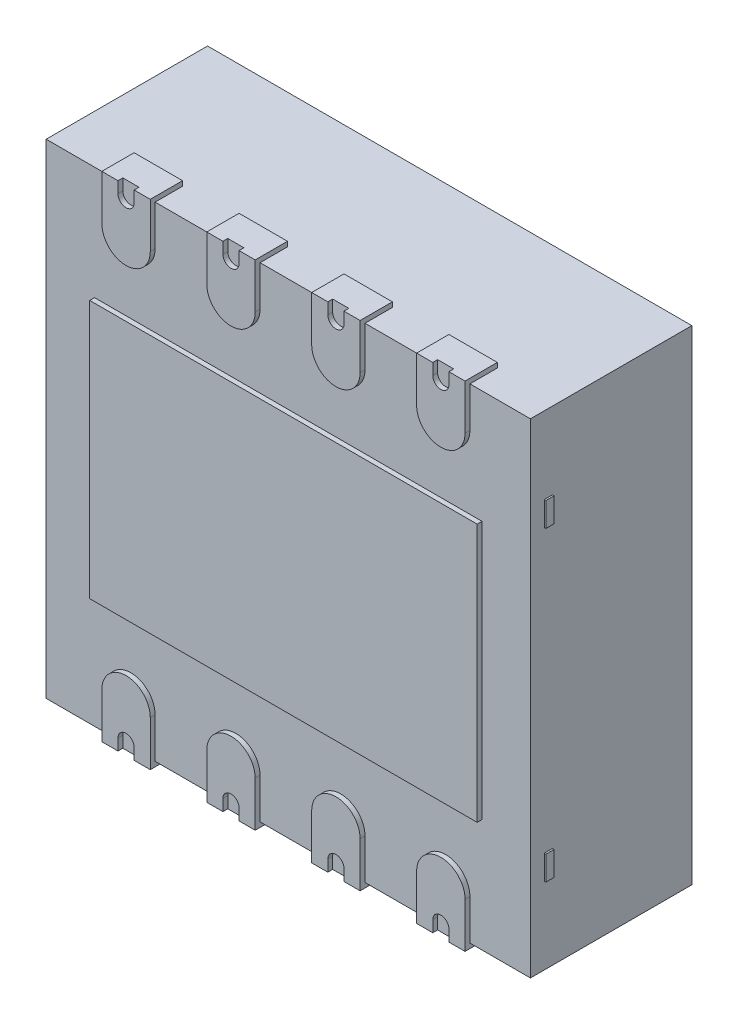
SolidWorks part; units mm, degrees
ref_plane "Front Plane" through (0, 0, 0) normal (0, 0, 1) x (1, 0, 0)
ref_plane "Top Plane" through (0, 0, 0) normal (0, 1, 0) x (1, 0, 0)
ref_plane "Right Plane" through (0, 0, 0) normal (1, 0, 0) x (0, 0, -1)
sketch "Sketch1" plane through (0, 0, 0) normal (0, 0, 1) x (1, 0, 0)
  line L1 (1.5, 1.5) -> (-1.5, 1.5)
  line L2 (1.5, 1.5) -> (1.5, -1.5)
  line L3 (1.5, -1.5) -> (-1.5, -1.5)
  line L4 (-1.5, 1.5) -> (-1.5, -1.5)
  line L5 (1.5, 1.5) -> (-1.5, -1.5) construction
  line L6 (1.5, -1.5) -> (-1.5, 1.5) construction
  point P0 (0, 0)
  dimension "D1" = 3
  dimension "D2" = 3
extrude "Boss-Extrude1" add sketch "Sketch1" against normal blind 1
sketch "Sketch2" plane through (0, 0, 0) normal (0, 0, 1) x (-1, 0, 0)
  line L0 (-0.975, 1.25) -> (-0.975, 1.6035) construction
  line L1 (1.2, 0.8) -> (-1.2, 0.8)
  line L2 (1.2, 0.8) -> (1.2, -0.8)
  line L3 (1.2, -0.8) -> (-1.2, -0.8)
  line L4 (-1.2, 0.8) -> (-1.2, -0.8)
  line L5 (1.2, 0.8) -> (-1.2, -0.8) construction
  line L6 (1.2, -0.8) -> (-1.2, 0.8) construction
  line L7 (-1.125, 1.25) -> (-1.125, 1.6035)
  line L8 (-0.825, 1.25) -> (-0.825, 1.6035)
  line L9 (1.5, 1.5) -> (-1.5, 1.5) construction
  line L10 (-0.175, 1.25) -> (-0.175, 1.6035)
  line L11 (-0.475, 1.25) -> (-0.475, 1.6035)
  line L12 (-0.325, 1.25) -> (-0.325, 1.6035) construction
  line L13 (0.475, 1.25) -> (0.475, 1.6035)
  line L14 (0.175, 1.25) -> (0.175, 1.6035)
  line L15 (0.325, 1.25) -> (0.325, 1.6035) construction
  line L16 (1.125, 1.25) -> (1.125, 1.6035)
  line L17 (0.825, 1.25) -> (0.825, 1.6035)
  line L18 (0.975, 1.25) -> (0.975, 1.6035) construction
  line L19 (0, 0) -> (0.825, 0) construction
  line L20 (-0.975, -1.25) -> (-0.975, -1.6035) construction
  line L21 (-1.125, -1.25) -> (-1.125, -1.6035)
  line L22 (-0.825, -1.25) -> (-0.825, -1.6035)
  line L23 (-0.325, -1.25) -> (-0.325, -1.6035) construction
  line L24 (-0.475, -1.25) -> (-0.475, -1.6035)
  line L25 (-0.175, -1.25) -> (-0.175, -1.6035)
  line L26 (0.325, -1.25) -> (0.325, -1.6035) construction
  line L27 (0.175, -1.25) -> (0.175, -1.6035)
  line L28 (0.475, -1.25) -> (0.475, -1.6035)
  line L29 (0.975, -1.25) -> (0.975, -1.6035) construction
  line L30 (0.825, -1.25) -> (0.825, -1.6035)
  line L31 (1.125, -1.25) -> (1.125, -1.6035)
  arc A0 (-1.125, 1.25) -> (-0.825, 1.25) centre (-0.975, 1.25) ccw
  arc A1 (-0.825, 1.6035) -> (-1.125, 1.6035) centre (-0.975, 1.6035) ccw
  arc A2 (-0.475, 1.25) -> (-0.175, 1.25) centre (-0.325, 1.25) ccw
  arc A3 (-0.175, 1.6035) -> (-0.475, 1.6035) centre (-0.325, 1.6035) ccw
  arc A4 (0.175, 1.25) -> (0.475, 1.25) centre (0.325, 1.25) ccw
  arc A5 (0.475, 1.6035) -> (0.175, 1.6035) centre (0.325, 1.6035) ccw
  arc A6 (0.825, 1.25) -> (1.125, 1.25) centre (0.975, 1.25) ccw
  arc A7 (1.125, 1.6035) -> (0.825, 1.6035) centre (0.975, 1.6035) ccw
  arc A8 (-1.125, -1.25) -> (-0.825, -1.25) centre (-0.975, -1.25) cw
  arc A9 (-0.825, -1.6035) -> (-1.125, -1.6035) centre (-0.975, -1.6035) cw
  arc A10 (-0.475, -1.25) -> (-0.175, -1.25) centre (-0.325, -1.25) cw
  arc A11 (-0.175, -1.6035) -> (-0.475, -1.6035) centre (-0.325, -1.6035) cw
  arc A12 (0.175, -1.25) -> (0.475, -1.25) centre (0.325, -1.25) cw
  arc A13 (0.475, -1.6035) -> (0.175, -1.6035) centre (0.325, -1.6035) cw
  arc A14 (0.825, -1.25) -> (1.125, -1.25) centre (0.975, -1.25) cw
  arc A15 (1.125, -1.6035) -> (0.825, -1.6035) centre (0.975, -1.6035) cw
  point P0 (0, 0)
  point P8 (-0.975, 1.4268)
  point P13 (-0.975, 1.1)
  point P19 (-0.325, 1.4268)
  point P26 (0.325, 1.4268)
  point P33 (0.975, 1.4268)
  point P41 (-0.975, -1.4268)
  point P48 (-0.325, -1.4268)
  point P55 (0.325, -1.4268)
  point P62 (0.975, -1.4268)
  dimension "D1" = 1.6
  dimension "D2" = 2.4
  dimension "D3" = 0.3
  dimension "D4" = 0.4
  dimension "D5" = 0.975
  dimension "D6" = 4
extrude "Boss-Extrude2" add sketch "Sketch2" along normal blind 0.03
sketch "Sketch4" plane through (0, 0, -1) normal (0, 0, -1) x (-1, 0, 0)
  line L1 (1.5, 1.5) -> (-1.5, 1.5)
  line L2 (1.5, 1.5) -> (1.5, -1.5)
  line L3 (1.5, -1.5) -> (-1.5, -1.5)
  line L4 (-1.5, 1.5) -> (-1.5, -1.5)
  line L5 (-2.0468, 1.8988) -> (1.8937, 1.8988)
  line L6 (-2.0468, 1.8988) -> (-2.0468, -1.9448)
  line L7 (-2.0468, -1.9448) -> (1.8937, -1.9448)
  line L8 (1.8937, 1.8988) -> (1.8937, -1.9448)
extrude "Cut-Extrude1" cut sketch "Sketch4" against normal blind 60.05
sketch "Sketch7" plane through (0, -1.5, 0) normal (0, -1, 0) x (1, 0, 0)
  line L0 (0.825, 0.03) -> (0.825, 0) construction
  line L1 (1.125, -0.17) -> (0.825, -0.17)
  line L2 (1.125, -0.17) -> (1.125, 0.03)
  line L3 (1.125, 0.03) -> (0.825, 0.03)
  line L4 (0.825, -0.17) -> (0.825, 0.03)
  line L5 (0.175, 0.03) -> (0.175, 0) construction
  line L6 (0.475, -0.17) -> (0.175, -0.17)
  line L7 (0.475, -0.17) -> (0.475, 0.03)
  line L8 (0.475, 0.03) -> (0.175, 0.03)
  line L9 (0.175, -0.17) -> (0.175, 0.03)
  line L10 (-0.475, 0.03) -> (-0.475, 0) construction
  line L11 (-0.175, -0.17) -> (-0.475, -0.17)
  line L12 (-0.175, -0.17) -> (-0.175, 0.03)
  line L13 (-0.175, 0.03) -> (-0.475, 0.03)
  line L14 (-0.475, -0.17) -> (-0.475, 0.03)
  line L15 (-1.125, 0.03) -> (-1.125, 0) construction
  line L16 (-0.825, -0.17) -> (-1.125, -0.17)
  line L17 (-0.825, -0.17) -> (-0.825, 0.03)
  line L18 (-0.825, 0.03) -> (-1.125, 0.03)
  line L19 (-1.125, -0.17) -> (-1.125, 0.03)
  point P7 (0.825, 0.015)
  point P22 (-0.475, 0.015)
  dimension "D1" = 0
  dimension "D2" = 0
  dimension "D3" = 0
  dimension "D4" = 0
  dimension "D5" = 0.2
  dimension "D6" = 0.2
  dimension "D7" = 0.2
  dimension "D8" = 0.2
extrude "Boss-Extrude3" add sketch "Sketch7" along normal blind 0.03
mirror "Mirror1" about plane through (0, 0, 0) normal (0, 1, 0) of "Boss-Extrude3"
sketch "Sketch8" plane through (0, 0, 0.03) normal (0, 0, 1) x (-1, 0, 0)
  line L0 (-0.975, 1.6098) -> (-0.975, 1.4598) construction
  line L1 (-0.925, 1.6098) -> (-0.925, 1.4598)
  line L2 (-1.025, 1.6098) -> (-1.025, 1.4598)
  line L3 (-0.375, 1.6098) -> (-0.375, 1.4598)
  line L6 (-0.275, 1.6098) -> (-0.275, 1.4598)
  line L9 (-0.325, 1.6098) -> (-0.325, 1.4598) construction
  line L13 (0.275, 1.6098) -> (0.275, 1.4598)
  line L15 (0.375, 1.6098) -> (0.375, 1.4598)
  line L16 (0.325, 1.6098) -> (0.325, 1.4598) construction
  line L17 (0.925, 1.6098) -> (0.925, 1.4598)
  line L18 (1.025, 1.6098) -> (1.025, 1.4598)
  line L19 (0.975, 1.6098) -> (0.975, 1.4598) construction
  line L20 (0, 0) -> (0.4114, 0) construction
  line L21 (-0.975, -1.6098) -> (-0.975, -1.4598) construction
  line L22 (-0.925, -1.6098) -> (-0.925, -1.4598)
  line L23 (-1.025, -1.6098) -> (-1.025, -1.4598)
  line L24 (-0.325, -1.6098) -> (-0.325, -1.4598) construction
  line L25 (-0.275, -1.6098) -> (-0.275, -1.4598)
  line L26 (-0.375, -1.6098) -> (-0.375, -1.4598)
  line L27 (0.325, -1.6098) -> (0.325, -1.4598) construction
  line L28 (0.375, -1.6098) -> (0.375, -1.4598)
  line L29 (0.275, -1.6098) -> (0.275, -1.4598)
  line L30 (0.975, -1.6098) -> (0.975, -1.4598) construction
  line L31 (1.025, -1.6098) -> (1.025, -1.4598)
  line L32 (0.925, -1.6098) -> (0.925, -1.4598)
  arc A0 (-0.925, 1.6098) -> (-1.025, 1.6098) centre (-0.975, 1.6098) ccw
  arc A1 (-1.025, 1.4598) -> (-0.925, 1.4598) centre (-0.975, 1.4598) ccw
  arc A8 (-0.275, 1.6098) -> (-0.375, 1.6098) centre (-0.325, 1.6098) ccw
  arc A9 (-0.375, 1.4598) -> (-0.275, 1.4598) centre (-0.325, 1.4598) ccw
  arc A10 (0.375, 1.6098) -> (0.275, 1.6098) centre (0.325, 1.6098) ccw
  arc A11 (0.275, 1.4598) -> (0.375, 1.4598) centre (0.325, 1.4598) ccw
  arc A12 (1.025, 1.6098) -> (0.925, 1.6098) centre (0.975, 1.6098) ccw
  arc A13 (0.925, 1.4598) -> (1.025, 1.4598) centre (0.975, 1.4598) ccw
  arc A14 (-0.925, -1.6098) -> (-1.025, -1.6098) centre (-0.975, -1.6098) cw
  arc A15 (-1.025, -1.4598) -> (-0.925, -1.4598) centre (-0.975, -1.4598) cw
  arc A16 (-0.275, -1.6098) -> (-0.375, -1.6098) centre (-0.325, -1.6098) cw
  arc A17 (-0.375, -1.4598) -> (-0.275, -1.4598) centre (-0.325, -1.4598) cw
  arc A18 (0.375, -1.6098) -> (0.275, -1.6098) centre (0.325, -1.6098) cw
  arc A19 (0.275, -1.4598) -> (0.375, -1.4598) centre (0.325, -1.4598) cw
  arc A20 (1.025, -1.6098) -> (0.925, -1.6098) centre (0.975, -1.6098) cw
  arc A21 (0.925, -1.4598) -> (1.025, -1.4598) centre (0.975, -1.4598) cw
  point P2 (-0.975, 1.5348)
  point P11 (-0.325, 1.5348)
  point P18 (0.325, 1.5348)
  point P25 (0.975, 1.5348)
  point P32 (-0.975, -1.5348)
  point P40 (-0.325, -1.5348)
  point P47 (0.325, -1.5348)
  point P54 (0.975, -1.5348)
  dimension "D1" = 0.05
  dimension "D2" = 4
  dimension "D3" = 0.15
extrude "Cut-Extrude2" cut sketch "Sketch8" against normal blind 0.03
sketch "Sketch9" plane through (-1.5, 0, 0) normal (-1, 0, 0) x (0, 0, 1)
  line L0 (0, 0) -> (-0.4231, 0) construction
  line L1 (-0.0858, 1.0236) -> (-0.0858, 0.8736)
  line L2 (-0.0858, 1.0236) -> (-0.1358, 1.0236)
  line L3 (-0.1358, 1.0236) -> (-0.1358, 0.8736)
  line L4 (-0.0858, 0.8736) -> (-0.1358, 0.8736)
  line L5 (-0.0858, -0.8736) -> (-0.1358, -0.8736)
  line L6 (-0.1358, -1.0236) -> (-0.1358, -0.8736)
  line L7 (-0.0858, -1.0236) -> (-0.1358, -1.0236)
  line L8 (-0.0858, -1.0236) -> (-0.0858, -0.8736)
  dimension "D1" = 0.15
  dimension "D2" = 0.05
extrude "Boss-Extrude4" add sketch "Sketch9" along normal blind 0.01
mirror "Mirror2" about plane through (0, 0, 0) normal (1, 0, 0) of "Boss-Extrude4"
sketch "Sketch11" plane through (0, 0, -1) normal (0, 0, -1) x (-1, 0, 0)
  line L0 (70.7212, 256.2979) -> (518.7212, 256.2979) construction
  line L54 (-0.8059, 1.0381) -> (-0.4233, 0.6054)
  line L55 (-0.3623, 0.9997) -> (-0.1188, 0.9997)
  line L56 (0.473, 0.2478) -> (0.2316, 0.2478)
  line L57 (-0.4233, 1.0381) -> (-0.0972, 1.0381)
  line L58 (-0.7882, 0.654) -> (-0.7882, 0.2148)
  line L59 (-0.1188, 0.9997) -> (0.0552, 0.7211)
  line L60 (-0.0933, 0.2106) -> (-0.3961, 0.2106)
  line L61 (-0.7882, 0.2148) -> (-1.0676, 0.2148)
  line L62 (0.5173, 0.9997) -> (0.9108, 0.9942)
  line L63 (0.5012, 0.8902) -> (0.5012, 0.6704)
  line L64 (0.9437, 0.5264) -> (0.5435, 0.5264)
  line L65 (-1.0282, 0.2545) -> (-1.0282, 0.9912)
  line L66 (0.5397, 0.8504) -> (0.8294, 0.8504)
  line L67 (1.0527, 0.8482) -> (1.0507, 0.7013)
  line L68 (0.8774, 0.8024) -> (0.8774, 0.7608)
  line L69 (-1.0676, 0.2148) -> (-1.0676, 1.0381)
  line L70 (0.5435, 0.2064) -> (0.2018, 0.2064)
  line L71 (-0.1256, 0.6262) -> (-0.3623, 0.9997)
  line L72 (0.5012, 0.5594) -> (0.5012, 0.27)
  line L73 (0.2018, 1.0381) -> (0.9437, 1.0381)
  line L74 (-0.3744, 0.4818) -> (-0.3744, 0.9397)
  line L75 (0.2391, 0.6223) -> (0.473, 0.2478)
  line L76 (0.2018, 0.2064) -> (0.0526, 0.4469)
  line L77 (-0.3981, 0.2613) -> (-0.8255, 0.7578)
  line L78 (0.2887, 0.6223) -> (0.5173, 0.9997)
  line L79 (0.8742, 0.6704) -> (0.5012, 0.6704)
  line L80 (1.0877, 0.8941) -> (1.0877, 0.6704)
  line L81 (-0.3961, 0.2106) -> (-0.7882, 0.654)
  line L82 (0.0552, 0.5301) -> (-0.1126, 0.2502)
  line L83 (0.0526, 0.7966) -> (0.2018, 1.0381)
  line L84 (0.0552, 0.7211) -> (0.2223, 0.9997)
  line L85 (-0.3623, 0.2502) -> (-0.1256, 0.6262)
  line L86 (-0.3744, 0.9397) -> (-0.1788, 0.6262)
  line L87 (0.2223, 0.9997) -> (0.4653, 0.9997)
  line L88 (0.5397, 0.8504) -> (0.5397, 0.7128)
  line L89 (-0.1126, 0.2502) -> (-0.3623, 0.2502)
  line L90 (0.5397, 0.7128) -> (0.8294, 0.7128)
  line L91 (0.2316, 0.2478) -> (0.0552, 0.5301)
  line L92 (0.5012, 0.8902) -> (0.8742, 0.8902)
  line L93 (0.5435, 0.5264) -> (0.5435, 0.2064)
  line L94 (-0.8129, 0.9912) -> (-0.3744, 0.4818)
  line L95 (0.9222, 0.8422) -> (0.9222, 0.7184)
  line L96 (-0.0972, 1.0381) -> (0.0526, 0.7966)
  line L97 (0.0526, 0.4469) -> (-0.0933, 0.2106)
  line L98 (-0.8255, 0.2545) -> (-1.0282, 0.2545)
  line L99 (0.9067, 0.5594) -> (0.5012, 0.5594)
  line L100 (-1.0676, 1.0381) -> (-0.8059, 1.0381)
  line L101 (-0.1788, 0.6262) -> (-0.3981, 0.2613)
  line L102 (0.4653, 0.9997) -> (0.2391, 0.6223)
  line L103 (-0.4233, 0.6054) -> (-0.4233, 1.0381)
  line L104 (-1.0282, 0.9912) -> (-0.8129, 0.9912)
  line L105 (-0.8255, 0.7578) -> (-0.8255, 0.2545)
  line L106 (0.5012, 0.27) -> (0.2887, 0.6223)
  arc A8 (0.8742, 0.8902) -> (0.9222, 0.8422) centre (0.8742, 0.8422) cw
  arc A9 (0.9437, 1.0381) -> (1.0877, 0.8941) centre (0.9437, 0.8941) cw
  arc A10 (0.9222, 0.7184) -> (0.8742, 0.6704) centre (0.8742, 0.7184) cw
  arc A11 (1.0877, 0.6704) -> (0.9437, 0.5264) centre (0.9437, 0.6704) cw
  arc A12 (0.8294, 0.8504) -> (0.8774, 0.8024) centre (0.8294, 0.8024) cw
  arc A13 (1.0507, 0.7013) -> (0.9067, 0.5594) centre (0.9067, 0.7034) cw
  arc A14 (0.8294, 0.7128) -> (0.8774, 0.7608) centre (0.8294, 0.7608) ccw
  arc A15 (0.9108, 0.9942) -> (1.0527, 0.8482) centre (0.9087, 0.8502) cw
sketch "Sketch12" plane through (0, 0, -1) normal (0, 0, -1) x (-1, 0, 0)
  line L0 (-1.0422, -0.9486) -> (0.9798, -0.9486) construction
  text T0 "<b>TJA1443</b>" font "Century Gothic" height 0.4
extrude "Boss-Extrude9" add sketch "Sketch11" along normal blind 0.01 contours A11 L80 A9 L73 L83 L96 L57 L103 L54 L100 L69 L61 L58 L81 L60 L97 L76 L70 L93 L64 L87 L102 L75 L56 L91 L82 L89 L85 L71 L55 L59 L84 L77 L105 L98 L65 L104 L94 L74 L86 L101 L62 A15 L67 A13 L99 L72 L106 | A10 L95 A8 L92 L63 L79 A14 L90 L88 L66 A12 L68
extrude "Boss-Extrude10" add sketch "Sketch12" along normal blind 0.01
